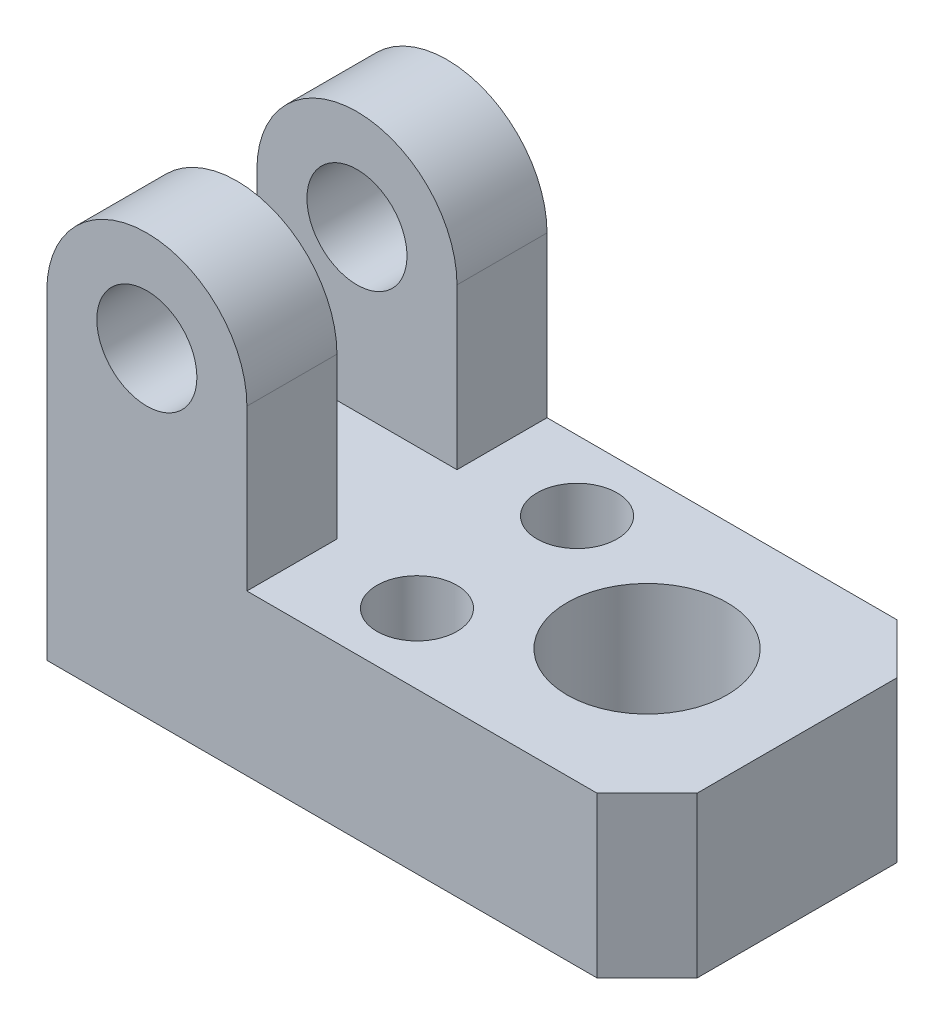
SolidWorks part; units mm, degrees
ref_plane "Front Plane" through (0, 0, 0) normal (0, 0, 1) x (1, 0, 0)
ref_plane "Top Plane" through (0, 0, 0) normal (0, 1, 0) x (1, 0, 0)
ref_plane "Right Plane" through (0, 0, 0) normal (1, 0, 0) x (0, 0, -1)
sketch "Sketch2" plane through (0, 0, 0) normal (0, 1, 0) x (1, 0, 0)
  line L1 (-30, -15) -> (30, -15)
  line L2 (-30, -15) -> (-30, 15)
  line L3 (-30, 15) -> (30, 15)
  line L4 (30, -15) -> (30, 15)
  line L5 (-30, -15) -> (30, 15) construction
  line L6 (-30, 15) -> (30, -15) construction
  point P0 (0, 0)
  dimension "D1" = 60
  dimension "D2" = 30
extrude "Boss-Extrude1" add sketch "Sketch2" along normal blind 16
sketch "Sketch3" plane through (0, 0, -15) normal (0, 0, -1) x (-1, 0, 0)
  line L1 (30, 16) -> (10, 16)
  line L2 (30, 16) -> (30, 32)
  line L4 (10, 16) -> (10, 32)
  arc A0 (30, 32) -> (10, 32) centre (20, 32) ccw
  dimension "D1" = 32
  dimension "D2" = 20
extrude "Boss-Extrude2" add sketch "Sketch3" against normal blind 9
sketch "Sketch4" plane through (0, 0, -15) normal (0, 0, -1) x (-1, 0, 0)
  circle A0 centre (20, 32) radius 5
  dimension "D1" = 10
extrude "Cut-Extrude1" cut sketch "Sketch4" against normal through all
mirror "Mirror1" about plane through (0, 0, 0) normal (0, 0, 1) of "Cut-Extrude1", "Boss-Extrude2"
sketch "Sketch5" plane through (0, 16, 0) normal (0, 1, 0) x (1, 0, 0)
  line L0 (-10, -6) -> (-10, -15) construction
  line L3 (-23.1, 0) -> (23.1, 0) construction
  circle A0 centre (15, 0) radius 8
  circle A1 centre (0, -8) radius 4
  circle A3 centre (0, 8) radius 4
  dimension "D3" = 8
  dimension "D4" = 16
  dimension "D1" = 16
  dimension "D5" = 10
  dimension "D7" = 25
extrude "Cut-Extrude2" cut sketch "Sketch5" against normal through all
chamfer "Chamfer1" distance 5 angle 45 2 edges at (30, 8, 15) (30, 8, -15)
